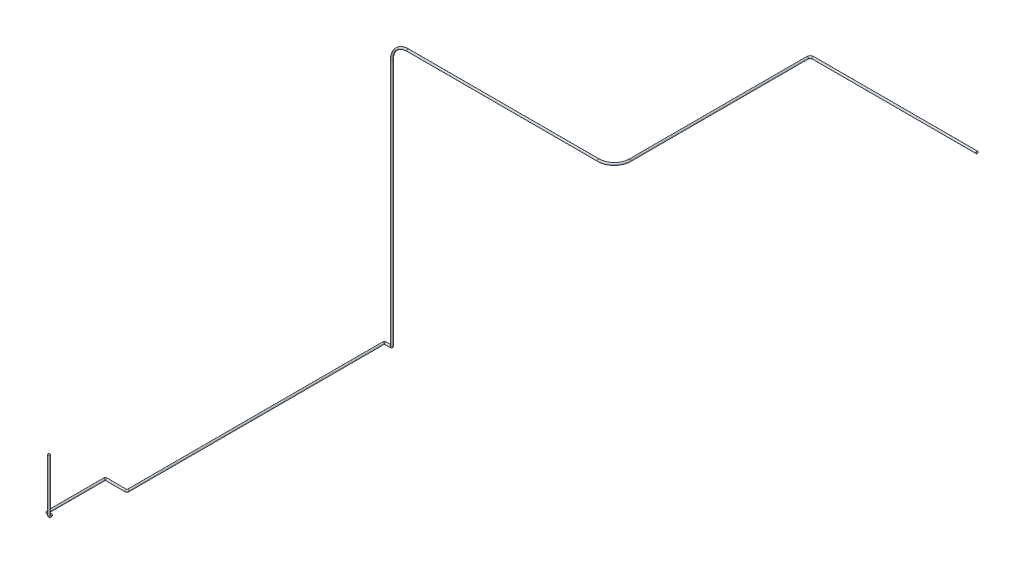
SolidWorks part; units mm, degrees
ref_plane "Alzado" through (0, 0, 0) normal (0, 0, 1) x (1, 0, 0)
ref_plane "Planta" through (0, 0, 0) normal (0, 1, 0) x (1, 0, 0)
ref_plane "Vista lateral" through (0, 0, 0) normal (1, 0, 0) x (0, 0, -1)
sketch "Croquis2" plane through (0, 0, 0) normal (0, 1, 0) x (1, 0, 0)
  circle A0 centre (0, 0) radius 18
  dimension "D1" = 36
extrude "Saliente-Extruir1" add sketch "Croquis2" against normal blind 50
sketch3d "Croquis3D1"
  line L0 (0, -50, 0) -> (0, -901, 0)
  line L1 (0, -50, 0) -> (0, 0, 0) construction
  line L2 (0, -920, -19) -> (0, -920, -21)
  line L3 (-19, -920, -40) -> (-61, -920, -40)
  line L4 (-80, -920, -59) -> (-80, -920, -1021)
  line L5 (-61, -920, -1040) -> (271, -920, -1040)
  line L6 (290, -920, -1059) -> (290, -920, -5421)
  line L7 (309, -920, -5440) -> (401, -920, -5440)
  line L8 (420, -901, -5440) -> (420, 3340, -5440)
  line L9 (690, 3610, -5440) -> (3950, 3610, -5440)
  line L10 (4220, 3610, -5710) -> (4220, 3610, -8740)
  line L11 (4270, 3610, -8790) -> (7070, 3610, -8790)
  arc A0 (271, -920, -1040) -> (290, -920, -1059) centre (271, -920, -1059) ccw
  arc A1 (-80, -920, -1021) -> (-61, -920, -1040) centre (-61, -920, -1021) ccw
  arc A2 (-61, -920, -40) -> (-80, -920, -59) centre (-61, -920, -59) ccw
  arc A3 (0, -920, -21) -> (-19, -920, -40) centre (-19, -920, -21) ccw
  arc A4 (0, -901, 0) -> (0, -920, -19) centre (0, -901, -19) ccw
  arc A5 (401, -920, -5440) -> (420, -901, -5440) centre (401, -901, -5440) ccw
  arc A6 (290, -920, -5421) -> (309, -920, -5440) centre (309, -920, -5421) ccw
  arc A7 (3950, 3610, -5440) -> (4220, 3610, -5710) centre (3950, 3610, -5710) ccw
  arc A8 (420, 3340, -5440) -> (690, 3610, -5440) centre (690, 3340, -5440) ccw
  arc A9 (4220, 3610, -8740) -> (4270, 3610, -8790) centre (4270, 3610, -8740) ccw
  point P11 (290, -920, -1040)
  point P12 (271, -901, -1059)
  point P15 (-80, -920, -1040)
  point P16 (-61, -939, -1021)
  point P19 (-80, -920, -40)
  point P20 (-61, -939, -59)
  point P23 (0, -920, -40)
  point P24 (-19, -901, -21)
  point P27 (0, -920, 0)
  point P28 (19, -901, -19)
  point P35 (420, -920, -5440)
  point P36 (401, -901, -5421)
  point P39 (290, -920, -5440)
  point P40 (309, -939, -5421)
  point P43 (4220, 3610, -5440)
  point P44 (3950, 3880, -5710)
  point P47 (420, 3610, -5440)
  point P48 (690, 3340, -5710)
  point P52 (4220, 3610, -8790)
  point P53 (4270, 3560, -8740)
  dimension "D7" = 19
  dimension "D12" = 19
  dimension "D13" = 270
  dimension "D15" = 50
  dimension "D1" = 870
  dimension "D2" = 40
  dimension "D3" = 80
  dimension "D4" = 1000
  dimension "D5" = 370
  dimension "D6" = 4400
  dimension "D8" = 130
  dimension "D11" = 3350
  dimension "D9" = 4530
  dimension "D10" = 3800
  dimension "D14" = 2850
sketch "Croquis3" plane through (0, -50, 0) normal (0, -1, 0) x (1, 0, 0)
  circle A0 centre (0, 0) radius 18
  dimension "D1" = 36
sweep "Barrer1" add profiles "Croquis3" path "Croquis3D1"
